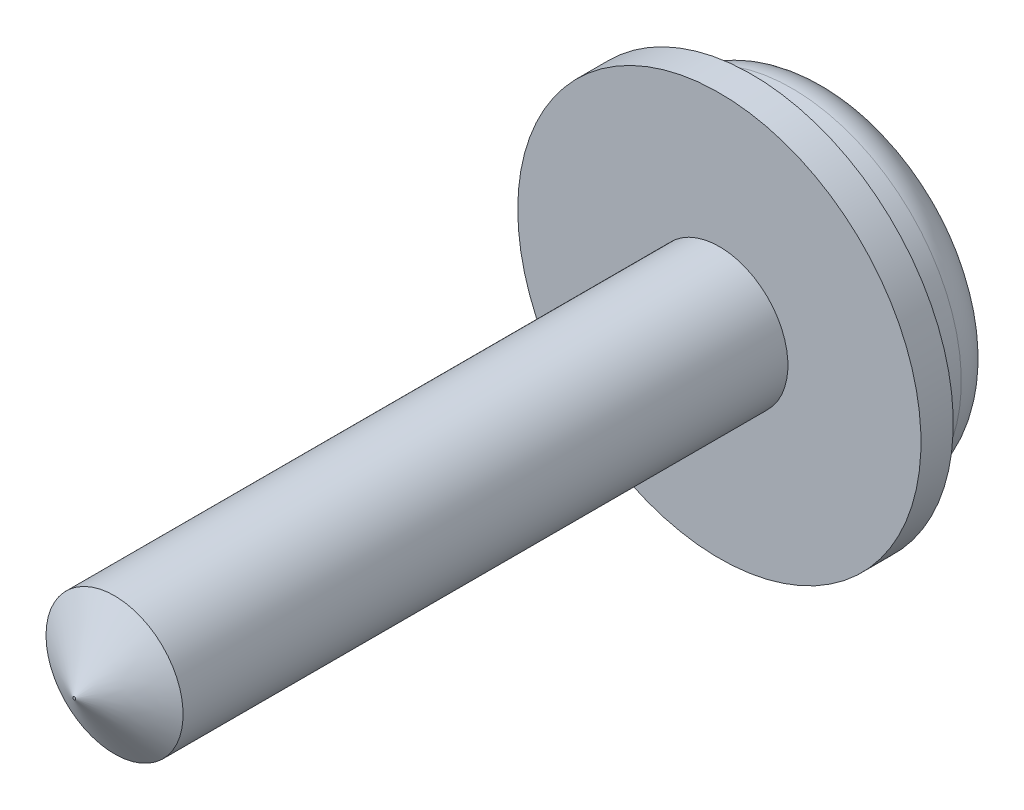
SolidWorks part; units mm, degrees
ref_plane "Plano frontal" through (0, 0, 0) normal (0, 0, 1) x (1, 0, 0)
ref_plane "Plano superior" through (0, 0, 0) normal (0, 1, 0) x (1, 0, 0)
ref_plane "Plano direito" through (0, 0, 0) normal (1, 0, 0) x (0, 0, -1)
sketch "Esboço1" plane through (0, 0, 0) normal (0, 0, 1) x (1, 0, 0)
  circle A0 centre (0, 0) radius 0.85
  dimension "D1" = 1.7
extrude "Ressalto-extrusão1" add sketch "Esboço1" along normal blind 8
chamfer "Chanfro1" distance 0.5 angle 59 1 edges at (0.85, 0, 8)
sketch "Esboço2" plane through (0, 0, 0) normal (0, 0, -1) x (-1, 0, 0)
  circle A0 centre (0, 0) radius 2.5
  dimension "D1" = 5
extrude "Ressalto-extrusão2" add sketch "Esboço2" along normal blind 0.4
sketch "Esboço3" plane through (0, 0, -0.4) normal (0, 0, -1) x (-1, 0, 0)
  circle A0 centre (0, 0) radius 2.1
  circle A1 centre (0, 0) radius 2.5 construction
  dimension "D1" = 0.4
extrude "Ressalto-extrusão3" add sketch "Esboço3" along normal blind 1
fillet "Filete1" radius 0.5 1 edges at (-2.1, 0, -1.4)
sketch "Esboço4" plane through (0, 0, -1.4) normal (0, 0, -1) x (-1, 0, 0)
  line L0 (-0.6, 0.3) -> (-1.15, 0.3)
  line L1 (0.3, -1.15) -> (-0.3, -1.15)
  line L2 (0.3, -1.15) -> (0.3, -0.6)
  line L3 (0.3, 1.15) -> (-0.3, 1.15)
  line L4 (-0.3, -1.15) -> (-0.3, -0.6)
  line L7 (1.15, -0.3) -> (0.6, -0.3)
  line L8 (1.15, -0.3) -> (1.15, 0.3)
  line L9 (1.15, 0.3) -> (0.6, 0.3)
  line L10 (-1.15, -0.3) -> (-1.15, 0.3)
  line L13 (0.3, 0.6) -> (0.3, 1.15)
  line L16 (-0.6, -0.3) -> (-1.15, -0.3)
  line L18 (-0.3, 0.6) -> (-0.3, 1.15)
  arc A0 (0.3, -0.6) -> (0.6, -0.3) centre (0.6, -0.6) cw
  arc A1 (0.3, 0.6) -> (0.6, 0.3) centre (0.6, 0.6) ccw
  arc A2 (-0.6, 0.3) -> (-0.3, 0.6) centre (-0.6, 0.6) ccw
  arc A3 (-0.6, -0.3) -> (-0.3, -0.6) centre (-0.6, -0.6) cw
  point P0 (0, 0)
  point P6 (0, 0)
  point P22 (-0.3, 0.3)
  dimension "D5" = 0.3
  dimension "D1" = 0.6
  dimension "D2" = 2.3
  dimension "D3" = 0.6
  dimension "D4" = 2.3
extrude "Corte-extrusão1" cut sketch "Esboço4" against normal blind 1
